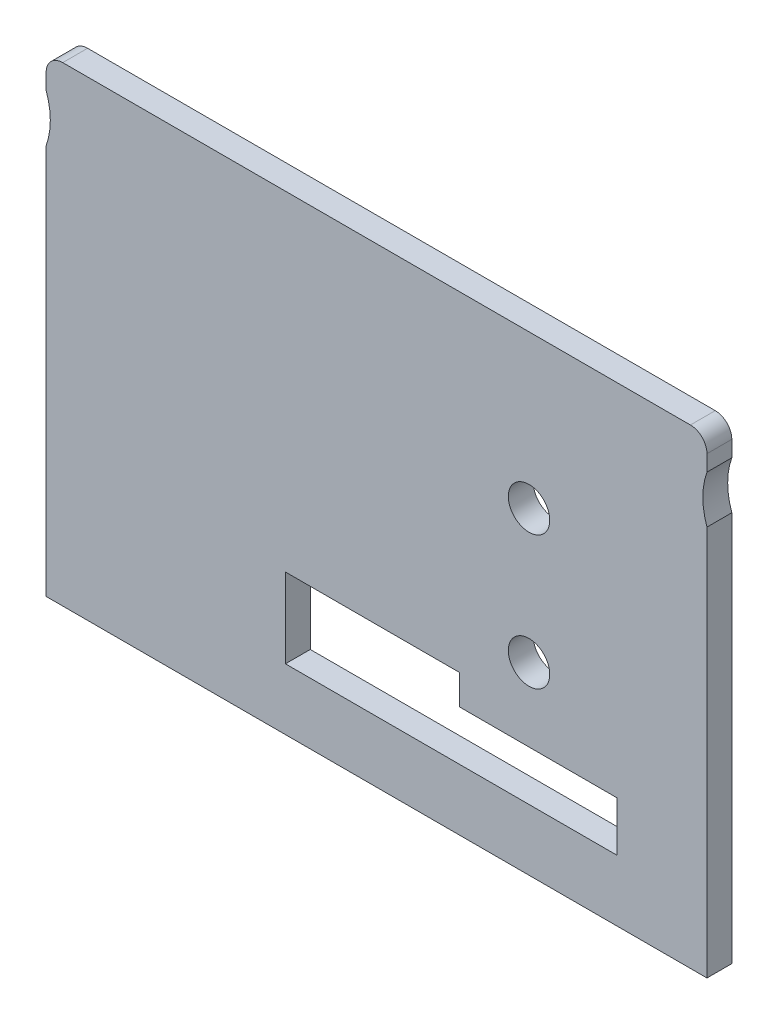
SolidWorks part; units mm, degrees
ref_plane "Front Plane" through (0, 0, 0) normal (0, 0, 1) x (1, 0, 0)
ref_plane "Top Plane" through (0, 0, 0) normal (0, 1, 0) x (1, 0, 0)
ref_plane "Right Plane" through (0, 0, 0) normal (1, 0, 0) x (0, 0, -1)
sketch "Sketch2" plane through (0, 0, 0) normal (0, 0, 1) x (1, 0, 0)
  line L0 (29, 7.4) -> (29, 17)
  line L1 (0, 0) -> (80, 0)
  line L2 (0, 0) -> (0, 56.8)
  line L3 (0, 56.8) -> (80, 56.8)
  line L4 (80, 0) -> (80, 56.8)
  line L5 (29, 17) -> (50, 17)
  line L6 (50, 17) -> (50, 13.4)
  line L7 (50, 13.4) -> (69, 13.4)
  line L8 (69, 13.4) -> (69, 7.4)
  line L9 (69, 7.4) -> (29, 7.4)
  circle A0 centre (58.4, 38.35) radius 2.5
  circle A1 centre (58.4, 22.25) radius 2.5
  dimension "D3" = 21.6
  dimension "D6" = 5
  dimension "D1" = 80
  dimension "D2" = 56.8
  dimension "D4" = 22.25
  dimension "D5" = 38.35
  dimension "D7" = 21
  dimension "D8" = 29
  dimension "D9" = 40
  dimension "D10" = 17
  dimension "D11" = 7.4
  dimension "D12" = 6
extrude "Boss-Extrude1" add sketch "Sketch2" along normal blind 3
sketch "Sketch4" plane through (0, 0, 3) normal (0, 0, 1) x (1, 0, 0)
  line L0 (0, 0) -> (80, 0) construction
  line L1 (0, 56.8) -> (0.125, 56.8)
  line L2 (0, 56.8) -> (0, 0)
  line L3 (0, 0) -> (0.125, 0)
  line L4 (0.125, 56.8) -> (0.125, 0)
  line L6 (80, 56.8) -> (79.875, 56.8)
  line L7 (80, 56.8) -> (80, 0)
  line L8 (80, 0) -> (79.875, 0)
  line L9 (79.875, 56.8) -> (79.875, 0)
  dimension "D1" = 0.125
extrude "Cut-Extrude2" cut sketch "Sketch4" against normal through all
sketch "Sketch3" plane through (0, 0, 3) normal (0, 0, 1) x (1, 0, 0)
  line L0 (40, 57) -> (40, 0) construction
  line L1 (0.125, 0) -> (0.125, 56.8) construction
  circle A0 centre (-7.875, 50) radius 8.5
  circle A1 centre (87.875, 50) radius 8.5
  dimension "D3" = 17
  dimension "D1" = 40
  dimension "D2" = 8
  dimension "D4" = 50
extrude "Cut-Extrude1" cut sketch "Sketch3" against normal through all
fillet "Fillet1" radius 2 2 edges at (0.125, 56.8, 1.5) (79.875, 56.8, 1.5)
